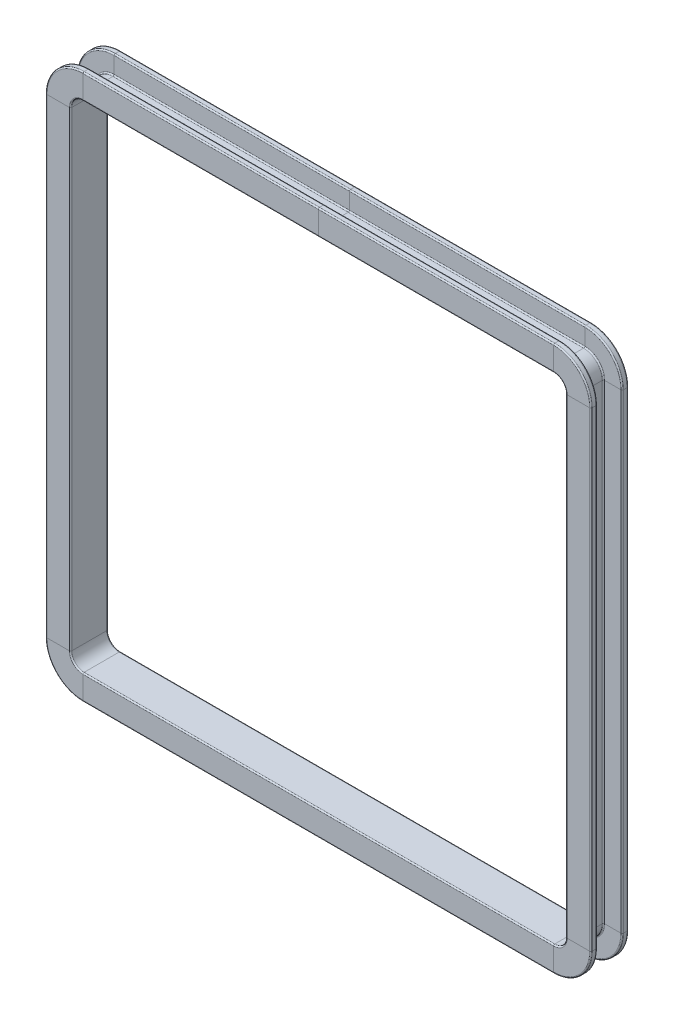
SolidWorks part; units mm, degrees
material "ABS"
ref_plane "Front Plane" through (0, 0, 0) normal (0, 0, 1) x (1, 0, 0)
ref_plane "Top Plane" through (0, 0, 0) normal (0, 1, 0) x (1, 0, 0)
ref_plane "Right Plane" through (0, 0, 0) normal (1, 0, 0) x (0, 0, -1)
sketch "Sketch2" plane through (0, 0, 0) normal (0, 0, 1) x (1, 0, 0)
  line L5 (855, 900) -> (-855, 900)
  line L6 (900, 855) -> (900, -855)
  line L7 (855, -900) -> (-855, -900)
  line L8 (-900, 855) -> (-900, -855)
  line L9 (900, 900) -> (-900, -900) construction
  line L10 (900, -900) -> (-900, 900) construction
  arc A0 (-855, -900) -> (-900, -855) centre (-855, -855) cw
  arc A1 (900, -855) -> (855, -900) centre (855, -855) cw
  arc A2 (855, 900) -> (900, 855) centre (855, 855) cw
  arc A3 (-855, 900) -> (-900, 855) centre (-855, 855) ccw
  point P0 (0, 0)
  point P20 (855, 900)
  dimension "D2" = 45
  dimension "D1" = 1800
sketch "Sketch3" plane through (0, 0, 0) normal (1, 0, 0) x (0, 0, -1)
  line L0 (0, -900) -> (0, 900) construction
  line L1 (0, 900) -> (0, 855) construction
  line L2 (-63.525, 900) -> (63.525, 900)
  line L3 (68.0625, 904.5375) -> (68.0625, 986.2125)
  line L5 (-45.375, 986.2125) -> (-45.375, 927.225)
  line L6 (-40.8375, 922.6875) -> (40.8375, 922.6875)
  line L7 (45.375, 927.225) -> (45.375, 986.2125)
  line L9 (-68.0625, 986.2125) -> (-68.0625, 904.5375)
  line L10 (-49.9125, 990.75) -> (-63.525, 990.75)
  line L11 (49.9125, 990.75) -> (63.525, 990.75)
  arc A0 (-63.525, 900) -> (-68.0625, 904.5375) centre (-63.525, 904.5375) cw
  arc A1 (63.525, 900) -> (68.0625, 904.5375) centre (63.525, 904.5375) ccw
  arc A2 (68.0625, 986.2125) -> (63.525, 990.75) centre (63.525, 986.2125) ccw
  arc A3 (45.375, 986.2125) -> (49.9125, 990.75) centre (49.9125, 986.2125) cw
  arc A4 (40.8375, 922.6875) -> (45.375, 927.225) centre (40.8375, 927.225) ccw
  arc A5 (-45.375, 927.225) -> (-40.8375, 922.6875) centre (-40.8375, 927.225) ccw
  arc A6 (-49.9125, 990.75) -> (-45.375, 986.2125) centre (-49.9125, 986.2125) cw
  arc A7 (-63.525, 990.75) -> (-68.0625, 986.2125) centre (-63.525, 986.2125) ccw
  point P0 (0, 900)
  point P11 (0, 900)
  point P23 (68.0625, 900)
  point P26 (68.0625, 990.75)
  point P29 (45.375, 990.75)
  point P32 (45.375, 922.6875)
  point P35 (-45.375, 922.6875)
  dimension "D5" = 4.5375
  dimension "D2" = 22.6875
  dimension "D1" = 90.75
  dimension "D3" = 22.6875
  dimension "D4" = 90.75
sweep "Sweep1" add profiles "Sketch3" path "Sketch2"
equation "\"A\"= 1.8m'Coil Case Length"
equation "\"D2@Sketch2\"=\"A\"/40"
equation "\"B\"= 82.5mm * 1.1'20 AWG Diam*100"
equation "\"D5@Sketch3\"=\"B\"/20"
equation "\"D2@Sketch3\"=\"B\"/4"
equation "\"D1@Sketch3\"=\"B\""
equation "\"D3@Sketch3\"=\"B\"/4"
equation "\"C\"= \"A\" + \"B\" * 3"
equation "\"D1@Sketch2\"=\"A\""
equation "\"D4@Sketch3\"=\"B\""
